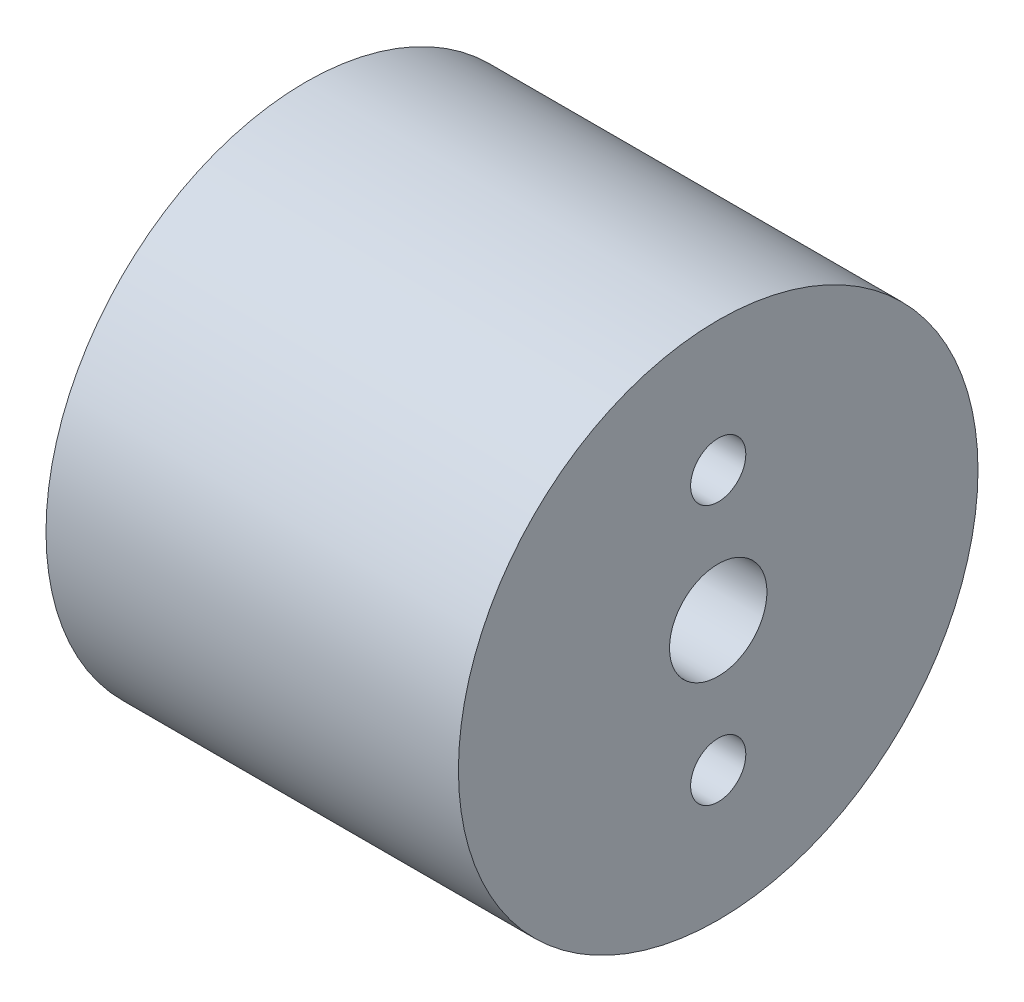
SolidWorks part; units mm, degrees
ref_plane "Front" through (0, 0, 0) normal (0, 0, 1) x (1, 0, 0)
ref_plane "Top" through (0, 0, 0) normal (0, 1, 0) x (1, 0, 0)
ref_plane "Right" through (0, 0, 0) normal (1, 0, 0) x (0, 0, -1)
sketch "Sketch1" plane through (0, 0, 0) normal (1, 0, 0) x (0, 0, -1)
  circle A0 centre (0, 0) radius 16
  circle A1 centre (0, 0) radius 11.4
extrude "Boss-Extrude1" add sketch "Sketch1" along normal blind 6.7
sketch "Sketch2" plane through (6.7, 0, 0) normal (1, 0, 0) x (0, 0, -1)
  circle A0 centre (0, 0) radius 10.7
  circle A2 centre (0, 0) radius 16
extrude "Boss-Extrude2" add sketch "Sketch2" along normal blind 3.2
sketch "Sketch3" plane through (9.9, 0, 0) normal (1, 0, 0) x (0, 0, -1)
  circle A0 centre (0, 0) radius 6.2
  circle A1 centre (0, 0) radius 16
extrude "Boss-Extrude3" add sketch "Sketch3" along normal blind 1
sketch "Sketch4" plane through (10.9, 0, 0) normal (1, 0, 0) x (0, 0, -1)
  circle A0 centre (0, 0) radius 4.7
  circle A1 centre (0, 0) radius 16
extrude "Boss-Extrude4" add sketch "Sketch4" along normal blind 7
sketch "Sketch5" plane through (17.9, 0, 0) normal (1, 0, 0) x (0, 0, -1)
  circle A0 centre (0, 0) radius 3
  circle A1 centre (0, 0) radius 16
extrude "Boss-Extrude5" add sketch "Sketch5" along normal blind 7.5
sketch "Sketch6" plane through (25.4, 0, 0) normal (1, 0, 0) x (0, 0, -1)
  circle A0 centre (0, 0) radius 8
  circle A1 centre (0, 8) radius 1.7
  circle A2 centre (0, -8) radius 1.7
extrude "Cut-Extrude1" cut sketch "Sketch6" against normal blind 25.4 contours A0 A1 | A0 A1 | A0 A2 | A0 A2
